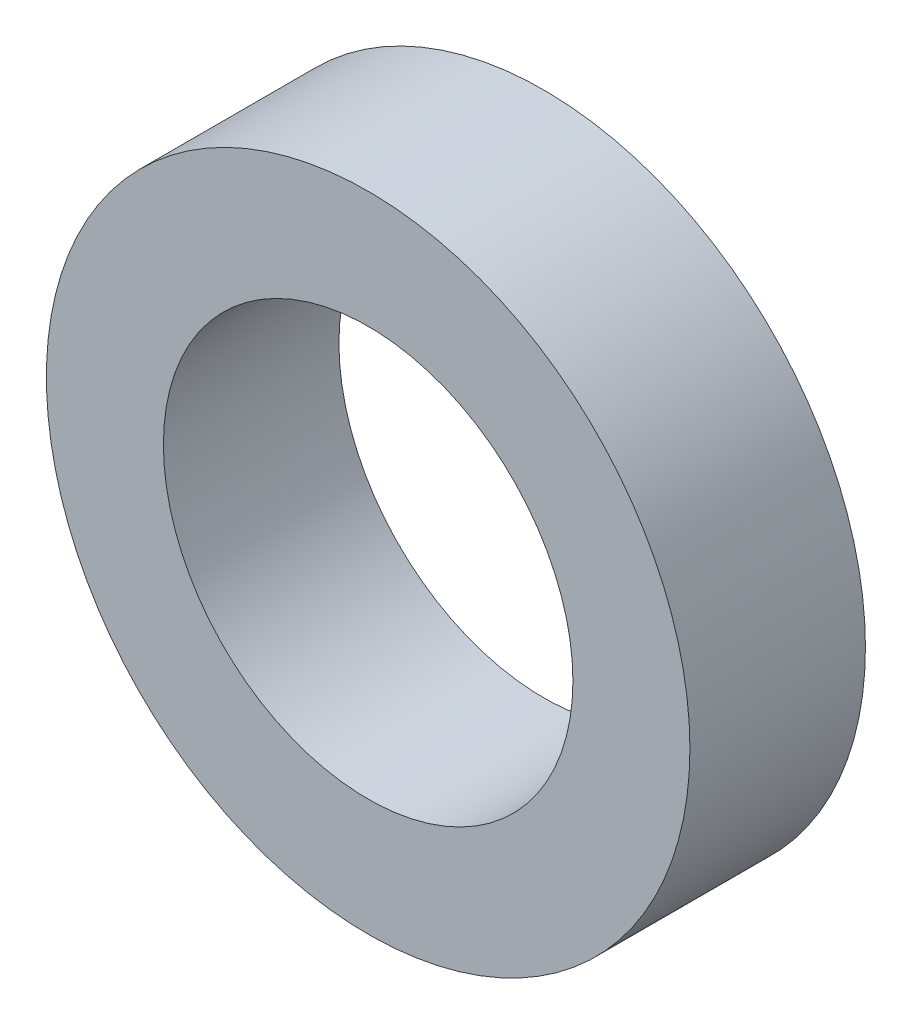
SolidWorks part; units mm, degrees
ref_plane "前视基准面" through (0, 0, 0) normal (0, 0, 1) x (1, 0, 0)
ref_plane "上视基准面" through (0, 0, 0) normal (0, 1, 0) x (1, 0, 0)
ref_plane "右视基准面" through (0, 0, 0) normal (1, 0, 0) x (0, 0, -1)
sketch "草图1" plane through (0, 0, 0) normal (0, 0, 1) x (1, 0, 0)
  circle A0 centre (0, 0) radius 5.5
  circle A1 centre (0, 0) radius 3.5
  dimension "D1" = 11
  dimension "D2" = 7
extrude "凸台-拉伸1" add sketch "草图1" along normal blind 3
